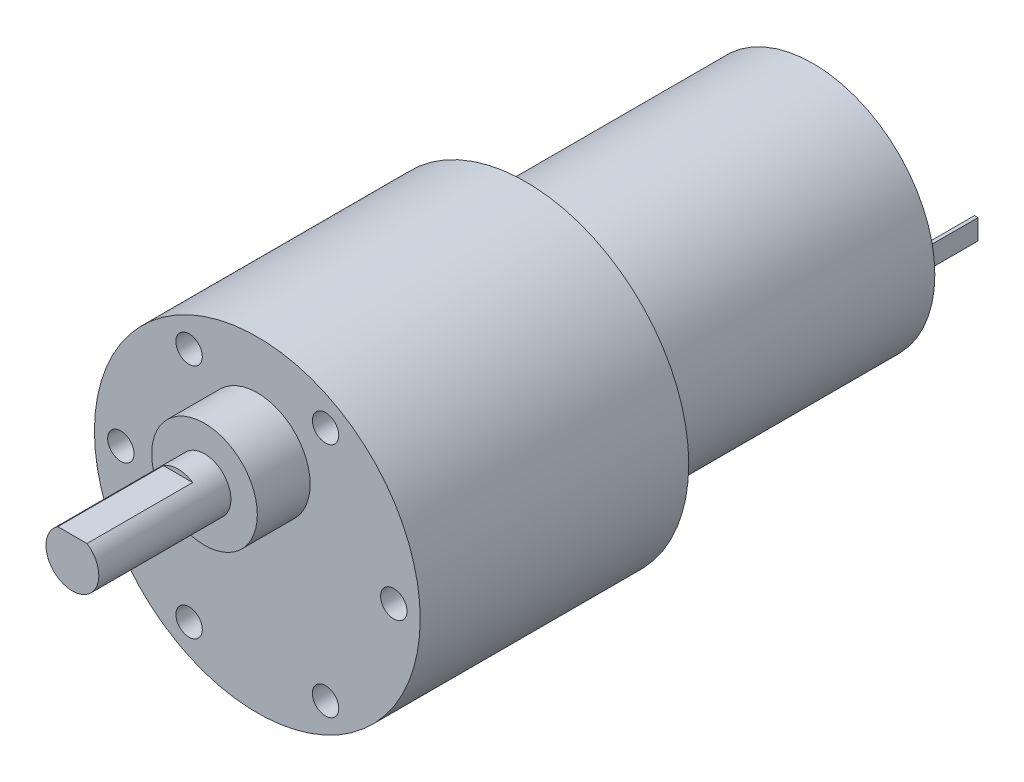
SolidWorks part; units mm, degrees
ref_plane "正面" through (0, 0, 0) normal (0, 0, 1) x (1, 0, 0)
ref_plane "平面" through (0, 0, 0) normal (0, 1, 0) x (1, 0, 0)
ref_plane "右側面" through (0, 0, 0) normal (1, 0, 0) x (0, 0, -1)
sketch "ｽｹｯﾁ1" plane through (0, 0, 0) normal (0, 0, 1) x (1, 0, 0)
  circle A0 centre (0, 0) radius 13.85
  dimension "D1" = 27.7
extrude "ﾎﾞｽ - 押し出し1" add sketch "ｽｹｯﾁ1" along normal blind 32.6
sketch "ｽｹｯﾁ2" plane through (0, 0, 32.6) normal (0, 0, 1) x (1, 0, 0)
  circle A0 centre (0, 0) radius 18.5
  dimension "D1" = 37
extrude "ﾎﾞｽ - 押し出し2" add sketch "ｽｹｯﾁ2" along normal blind 30.5
sketch "ｽｹｯﾁ3" plane through (0, 0, 63.1) normal (0, 0, 1) x (1, 0, 0)
  circle A0 centre (0, 7) radius 6
  dimension "D1" = 12
  dimension "D2" = 7
extrude "ﾎﾞｽ - 押し出し3" add sketch "ｽｹｯﾁ3" along normal blind 6
sketch "ｽｹｯﾁ4" plane through (0, 0, 69.1) normal (0, 0, 1) x (1, 0, 0)
  circle A0 centre (0, 7) radius 3
  dimension "D1" = 6
extrude "ﾎﾞｽ - 押し出し4" add sketch "ｽｹｯﾁ4" along normal blind 15
sketch "ｽｹｯﾁ5" plane through (0, 0, 84.1) normal (0, 0, 1) x (1, 0, 0)
  line L0 (-1.6583, 9.5) -> (1.6583, 9.5)
  arc A0 (-1.6583, 9.5) -> (1.6583, 9.5) centre (0, 7) cw
  circle A1 centre (0, 7) radius 3 construction
  dimension "D1" = 2.5
extrude "ｶｯﾄ - 押し出し1" cut sketch "ｽｹｯﾁ5" against normal blind 12
sketch "ｽｹｯﾁ6" plane through (0, 0, 63.1) normal (0, 0, 1) x (1, 0, 0)
  circle A0 centre (-15.5, 0) radius 1.5
  circle A1 centre (0, 0) radius 15.5 construction
  circle A2 centre (-7.75, 13.4234) radius 1.5
  circle A3 centre (7.75, 13.4234) radius 1.5
  circle A4 centre (15.5, 0) radius 1.5
  circle A5 centre (7.75, -13.4234) radius 1.5
  circle A6 centre (-7.75, -13.4234) radius 1.5
  point P17 (0, 0)
  dimension "D1" = 31
  dimension "D2" = 3
  dimension "D3" = 6
extrude "ｶｯﾄ - 押し出し2" cut sketch "ｽｹｯﾁ6" against normal blind 3.5
sketch "ｽｹｯﾁ7" plane through (0, 0, 0) normal (0, 0, -1) x (-1, 0, 0)
  circle A0 centre (0, 0) radius 5
  dimension "D1" = 10
extrude "ﾎﾞｽ - 押し出し5" add sketch "ｽｹｯﾁ7" along normal blind 2.6
sketch "ｽｹｯﾁ8" plane through (0, 0, -2.6) normal (0, 0, -1) x (-1, 0, 0)
  circle A0 centre (0, 0) radius 1.15
  dimension "D1" = 2.3
extrude "ﾎﾞｽ - 押し出し6" add sketch "ｽｹｯﾁ8" along normal blind 8.5 from surface at -2.6 starting at face at (-5, 0, 0)
sketch "ｽｹｯﾁ9" plane through (0, 0, 0) normal (0, 0, -1) x (-1, 0, 0)
  line L0 (0, 22.7928) -> (0, -25.5728) construction
  line L1 (11.85, -1.15) -> (11.45, -1.15)
  line L2 (-11.85, 1.15) -> (-11.45, 1.15)
  line L3 (-11.85, 1.15) -> (-11.85, -1.15)
  line L4 (-11.85, -1.15) -> (-11.45, -1.15)
  line L5 (-11.45, 1.15) -> (-11.45, -1.15)
  line L6 (-11.85, 1.15) -> (-11.45, -1.15) construction
  line L7 (-11.85, -1.15) -> (-11.45, 1.15) construction
  line L8 (11.45, 1.15) -> (11.45, -1.15)
  line L9 (11.85, 1.15) -> (11.45, 1.15)
  line L10 (11.85, 1.15) -> (11.85, -1.15)
  point P7 (-11.65, 0)
  dimension "D1" = 0.4
  dimension "D2" = 2.3
  dimension "D3" = 22.9
extrude "ﾎﾞｽ - 押し出し7" add sketch "ｽｹｯﾁ9" along normal blind 6.9
